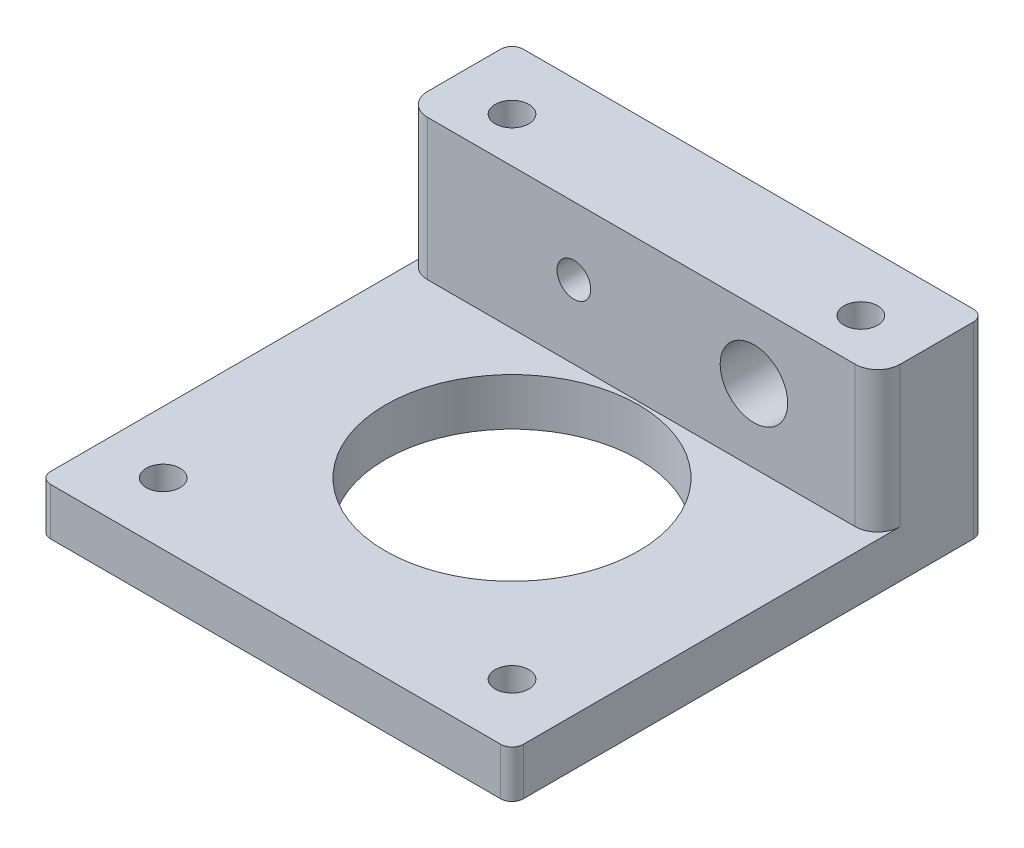
SolidWorks part; units mm, degrees
ref_plane "前视基准面" through (0, 0, 0) normal (0, 0, 1) x (1, 0, 0)
ref_plane "上视基准面" through (0, 0, 0) normal (0, 1, 0) x (1, 0, 0)
ref_plane "右视基准面" through (0, 0, 0) normal (1, 0, 0) x (0, 0, -1)
sketch "草图1" plane through (0, 0, 0) normal (0, 1, 0) x (1, 0, 0)
  line L0 (-15.5, 15.5) -> (-15.5, -15.5) construction
  line L1 (-21, 21) -> (21, 21)
  line L2 (-21, 21) -> (-21, -21)
  line L3 (-21, -21) -> (21, -21)
  line L4 (21, 21) -> (21, -21)
  line L5 (0, -21) -> (0, 21) construction
  line L6 (-21, 0) -> (21, 0) construction
  line L7 (-15.5, -15.5) -> (15.5, -15.5) construction
  line L8 (15.5, 15.5) -> (15.5, -15.5) construction
  line L9 (-15.5, 15.5) -> (15.5, 15.5) construction
  circle A0 centre (-15.5, 15.5) radius 1.5
  circle A1 centre (15.5, 15.5) radius 1.5
  circle A2 centre (-15.5, -15.5) radius 1.5
  circle A3 centre (15.5, -15.5) radius 1.5
  point P0 (0, 0)
  dimension "D3" = 3
  dimension "D1" = 42
  dimension "D2" = 31
extrude "凸台-拉伸1" add sketch "草图1" along normal blind 4.2
sketch "草图2" plane through (0, 4.2, 0) normal (0, 1, 0) x (1, 0, 0)
  line L0 (21, -21) -> (21, 21) construction
  line L1 (-21, 21) -> (21, 21)
  line L2 (-21, 21) -> (-21, 11.5)
  line L3 (-21, 11.5) -> (21, 11.5)
  line L4 (21, 21) -> (21, 11.5)
  line L5 (-21, 21) -> (21, 11.5) construction
  line L6 (-21, 11.5) -> (21, 21) construction
  circle A0 centre (-15.5, 15.5) radius 1.5 construction
  circle A1 centre (-15.5, 15.5) radius 1.5
  circle A2 centre (15.5, 15.5) radius 1.5 construction
  circle A3 centre (15.5, 15.5) radius 1.5
  point P4 (0, 16.25)
  dimension "D1" = 9.5
extrude "凸台-拉伸2" add sketch "草图2" along normal blind 12.5
sketch "草图3" plane through (0, 4.2, 0) normal (0, 1, 0) x (1, 0, 0)
  circle A0 centre (0, 0) radius 11.25
  dimension "D1" = 22.5
extrude "切除-拉伸1" cut sketch "草图3" against normal through all
sketch "草图4" plane through (0, 0, -21) normal (0, 0, -1) x (-1, 0, 0)
  line L0 (-21, 10.7) -> (21, 10.7) construction
  line L1 (-21, 16.7) -> (-21, 0) construction
  line L2 (21, 16.7) -> (21, 0) construction
  line L3 (-21, 16.7) -> (21, 16.7) construction
  circle A0 centre (-10, 10.7) radius 3
  circle A1 centre (6, 10.7) radius 1.5
  dimension "D2" = 6
  dimension "D3" = 3
  dimension "D1" = 6
  dimension "D4" = 15
  dimension "D5" = 16
extrude "切除-拉伸2" cut sketch "草图4" against normal through all
sketch "草图5" plane through (0, 0, -21) normal (0, 0, -1) x (-1, 0, 0)
  circle A1 centre (6, 10.7) radius 3.5
  dimension "D1" = 7
extrude "切除-拉伸3" cut sketch "草图5" against normal blind 2
fillet "圆角2" radius 1 4 edges at (-21, 2.1, 21) (21, 2.1, 21) (21, 8.35, -21) (-21, 8.35, -21)
fillet "圆角3" radius 2 2 edges at (21, 10.45, -11.5) (-21, 10.45, -11.5)
